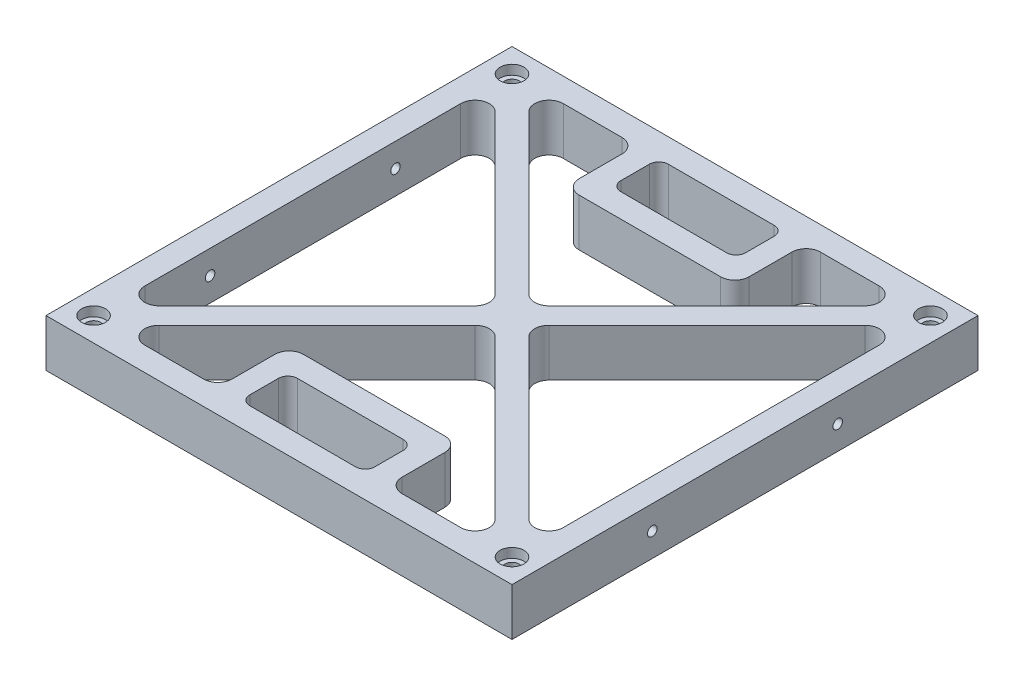
SolidWorks part; units mm, degrees
ref_plane "Front Plane" through (0, 0, 0) normal (0, 0, 1) x (1, 0, 0)
ref_plane "Top Plane" through (0, 0, 0) normal (0, 1, 0) x (1, 0, 0)
ref_plane "Right Plane" through (0, 0, 0) normal (1, 0, 0) x (0, 0, -1)
sketch "Sketch1" plane through (0, 0, 0) normal (0, 1, 0) x (1, 0, 0)
  line L1 (-53, 53) -> (53, 53)
  line L2 (-53, 53) -> (-53, -53)
  line L3 (-53, -53) -> (53, -53)
  line L4 (53, 53) -> (53, -53)
  line L5 (-53, 53) -> (53, -53) construction
  line L6 (-53, -53) -> (53, 53) construction
  point P0 (0, 0)
  dimension "D1" = 106
  dimension "D2" = 106
extrude "Boss-Extrude1" add sketch "Sketch1" along normal blind 10
sketch "Sketch3" plane through (0, 10, 0) normal (0, 1, 0) x (1, 0, 0)
  line L5 (-50, 50) -> (50, 50)
  line L6 (-50, 50) -> (-50, -50)
  line L7 (-50, -50) -> (50, -50)
  line L8 (50, 50) -> (50, -50)
  point P0 (0, 0)
  point P6 (0, 0)
sketch "Sketch12" plane through (53, 0, 0) normal (1, 0, 0) x (0, 0, -1)
  line L0 (-39, 10) -> (-39, 0)
  line L1 (-53, 10) -> (53, 10) construction
  line L2 (-39, 13) -> (-39, 3) construction
  line L3 (-53, 0) -> (53, 0) construction
  line L4 (39, 10) -> (39, 0)
  line L5 (39, 3) -> (39, 13) construction
  line L6 (-39, 10) -> (0, 10)
  line L7 (0, 10) -> (0, 0)
  line L8 (0, 10) -> (39, 10)
  line L9 (-19.5, 10) -> (-19.5, 0)
  line L10 (19.5, 10) -> (19.5, 0)
  circle A0 centre (-19.5, 5) radius 1.75
  circle A1 centre (19.5, 5) radius 1.75
  dimension "D1" = 3.5
extrude "Cut-Extrude9" cut sketch "Sketch12" against normal blind 1.5 contours L9 A0 | A1 L10 | A1 L10
sketch "Sketch14" plane through (51.5, 0, 0) normal (1, 0, 0) x (0, 0, -1)
  circle A0 centre (-19.5, 5) radius 1
  circle A1 centre (19.5, 5) radius 1
sketch "Sketch16" plane through (0, 0, 0) normal (0, -1, 0) x (1, 0, 0)
  line L1 (-49, -49) -> (49, -49) construction
  line L2 (-49, -49) -> (-49, 49) construction
  line L3 (-49, 49) -> (49, 49) construction
  line L4 (49, -49) -> (49, 49) construction
  point P0 (0, 0)
sketch "Sketch17" plane through (0, 0, 0) normal (0, -1, 0) x (1, 0, 0)
  line L0 (0, 3.5355) -> (40.4645, 44)
  line L1 (-49, -49) -> (49, -49)
  line L2 (-49, -49) -> (-49, 49)
  line L3 (-49, 49) -> (49, 49)
  line L4 (49, -49) -> (49, 49)
  line L5 (-44, -44) -> (44, -44)
  line L6 (-44, -44) -> (-44, 44)
  line L7 (-44, 44) -> (44, 44)
  line L8 (44, -44) -> (44, 44)
  line L9 (-13.1264, -44) -> (-13.1264, -34)
  line L11 (-44, -40.4645) -> (-3.5355, 0)
  line L12 (-40.4645, -44) -> (0, -3.5355)
  line L14 (-40.4645, 44) -> (0, 3.5355)
  line L15 (-44, 40.4645) -> (-3.5355, 0)
  line L16 (0, -3.5355) -> (40.4645, -44)
  line L17 (3.5355, 0) -> (44, -40.4645)
  line L18 (3.5355, 0) -> (44, 40.4645)
  line L19 (13.1264, -34) -> (-13.1264, -34)
  line L21 (-17.8692, -44) -> (-17.8692, -29)
  line L24 (17.8692, -29) -> (-17.8692, -29)
  line L25 (13.1264, -44) -> (13.1264, -34)
  line L27 (-3.5355, 0) -> (-14.3188, 0)
  line L28 (-17.8692, 44) -> (-17.8692, 29)
  line L29 (-13.1264, 44) -> (-13.1264, 34)
  line L30 (13.1264, 44) -> (13.1264, 34)
  line L31 (17.8692, -44) -> (17.8692, -29)
  line L32 (17.8692, 44) -> (17.8692, 29)
  line L33 (17.8692, 29) -> (-17.8692, 29)
  line L34 (13.1264, 34) -> (-13.1264, 34)
  point P0 (0, 0)
  point P6 (0, 0)
  point P12 (0, -44)
  point P18 (1.7678, -1.7678)
  point P24 (-1.7678, -1.7678)
  point P27 (0, -44)
  dimension "D1" = 98
  dimension "D2" = 98
  dimension "D3" = 10
  dimension "D4" = 15
sketch "Sketch18" plane through (0, 0, 0) normal (0, -1, 0) x (1, 0, 0)
  line L1 (-53, -53) -> (53, -53)
  line L2 (-53, -53) -> (-53, 53)
  line L3 (-53, 53) -> (53, 53)
  line L4 (53, -53) -> (53, 53)
  line L5 (-50, -50) -> (50, -50)
  line L6 (-50, -50) -> (-50, 50)
  line L7 (-50, 50) -> (50, 50)
  line L8 (50, -50) -> (50, 50)
  line L9 (-50, -50) -> (50, 50) construction
  line L10 (-50, 50) -> (50, -50) construction
  point P0 (0, 0)
  point P7 (0, 0)
extrude "Cut-Extrude14" cut sketch "Sketch18" against normal blind 10
sketch "Sketch20" plane through (50, 0, 0) normal (1, 0, 0) x (0, 0, -1)
  circle A0 centre (19.5, 5) radius 1
  circle A1 centre (-19.5, 5) radius 1
extrude "Cut-Extrude15" cut sketch "Sketch20" against normal blind 8 contours A0 | A1
sketch "Sketch21" plane through (-50, 0, 0) normal (-1, 0, 0) x (0, 0, 1)
  circle A0 centre (19.5, 5) radius 1
  circle A1 centre (-19.5, 5) radius 1
extrude "Cut-Extrude16" cut sketch "Sketch21" against normal blind 8
sketch "Sketch23" plane through (0, 0, 0) normal (0, -1, 0) x (1, 0, 0)
  line L1 (-50, 50) -> (50, 50)
  line L2 (-50, 50) -> (-50, -50)
  line L3 (-50, -50) -> (50, -50)
  line L4 (50, 50) -> (50, -50)
  line L5 (-49, 49) -> (49, 49)
  line L6 (-49, 49) -> (-49, -49)
  line L7 (-49, -49) -> (49, -49)
  line L8 (49, 49) -> (49, -49)
  point P0 (0, 0)
  point P7 (0, 0)
extrude "Cut-Extrude17" cut sketch "Sketch23" against normal blind 10
extrude "Cut-Extrude19" cut sketch "Sketch17" against normal blind 10
fillet "Fillet2" radius 3 12 edges at (-40.4645, 5, -44) (-44, 5, -40.4645) (-44, 5, 40.4645) (-40.4645, 5, 44) (40.4645, 5, -44) (44, 5, -40.4645) (44, 5, 40.4645) (40.4645, 5, 44) (0, 5, -3.5355) (-3.5355, 5, 0) (3.5355, 5, 0) (0, 5, 3.5355)
fillet "Fillet3" radius 3 8 edges at (-17.8692, 5, 44) (-17.8692, 5, 29) (17.8692, 5, 44) (17.8692, 5, 29) (-17.8692, 5, -44) (-17.8692, 5, -29) (17.8692, 5, -29) (17.8692, 5, -44)
fillet "Fillet4" radius 2 8 edges at (13.1264, 5, 44) (-13.1264, 5, 44) (-13.1264, 5, 34) (13.1264, 5, 34) (-13.1264, 5, -44) (13.1264, 5, -34) (-13.1264, 5, -34) (13.1264, 5, -44)
sketch "Sketch26" plane through (0, 10, 0) normal (0, 1, 0) x (1, 0, 0)
  line L1 (-44, 44) -> (44, 44) construction
  line L2 (-44, 44) -> (-44, -44) construction
  line L3 (-44, -44) -> (44, -44) construction
  line L4 (44, 44) -> (44, -44) construction
  circle A0 centre (44, -44) radius 1.5
  circle A1 centre (-44, -44) radius 1.5
  circle A2 centre (44, 44) radius 1.5
  circle A3 centre (-44, 44) radius 1.5
  point P0 (0, 0)
extrude "Cut-Extrude20" cut sketch "Sketch26" against normal blind 10
sketch "Sketch27" plane through (0, 10, 0) normal (0, 1, 0) x (1, 0, 0)
  circle A0 centre (44, -44) radius 2.5
  circle A1 centre (-44, -44) radius 2.5
  circle A2 centre (-44, 44) radius 2.5
  circle A3 centre (44, 44) radius 2.5
extrude "Cut-Extrude21" cut sketch "Sketch27" against normal blind 2
sketch "Sketch28" plane through (49, 0, 0) normal (1, 0, 0) x (0, 0, -1)
  line L1 (49, 0) -> (-49, 0)
  line L2 (49, 0) -> (49, 10)
  line L3 (49, 10) -> (-49, 10)
  line L4 (-49, 0) -> (-49, 10)
sketch "Sketch29" plane through (0, 0, 0) normal (0, -1, 0) x (1, 0, 0)
  line L1 (44, 44) -> (-44, 44) construction
  line L2 (44, 44) -> (44, -44) construction
  line L3 (44, -44) -> (-44, -44) construction
  line L4 (-44, 44) -> (-44, -44) construction
